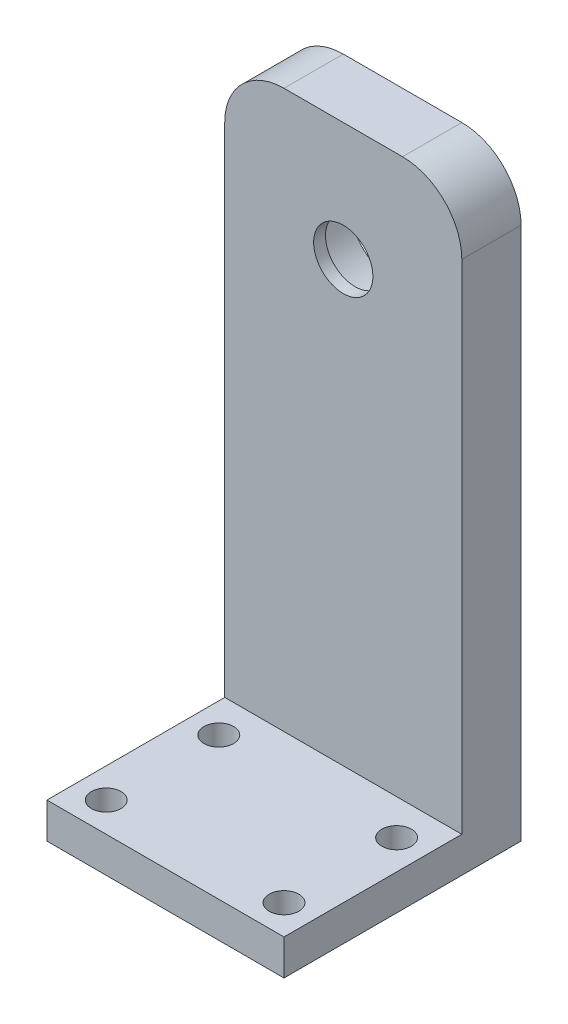
SolidWorks part; units mm, degrees
ref_plane "前视基准面" through (0, 0, 0) normal (0, 0, 1) x (1, 0, 0)
ref_plane "上视基准面" through (0, 0, 0) normal (0, 1, 0) x (1, 0, 0)
ref_plane "右视基准面" through (0, 0, 0) normal (1, 0, 0) x (0, 0, -1)
sketch "草图1" plane through (0, 0, 0) normal (0, 0, 1) x (1, 0, 0)
  line L0 (0, 17.9034) -> (0, -4.2573) construction
  line L1 (-13.2445, 0) -> (15.9947, 0) construction
  line L2 (-20, 15) -> (20, 15)
  line L3 (-20, 15) -> (-20, -15)
  line L4 (-20, -15) -> (20, -15)
  line L5 (20, 15) -> (20, -15)
  dimension "D1" = 40
  dimension "D2" = 30
  dimension "D3" = 20
  dimension "D4" = 15
extrude "凸台-拉伸1" add sketch "草图1" along normal blind 10
sketch "草图2" plane through (0, 0, 10) normal (0, 0, 1) x (1, 0, 0)
  line L0 (0, 19.1713) -> (0, -20.8604) construction
  line L1 (20, 15) -> (17.5, 15)
  line L2 (-5, 10) -> (-12.7402, 10)
  line L3 (20, 15) -> (-20, 15) construction
  line L4 (-20, 15) -> (-20, -15) construction
  line L5 (-20, 12.5) -> (-20, 15)
  line L6 (-20, 15) -> (-17.5, 15)
  line L7 (20, 12.5) -> (20, 15)
  line L9 (-20, -10) -> (20, -10)
  line L10 (-20, -10) -> (-20, -15)
  line L11 (-20, -15) -> (20, -15)
  line L12 (20, -10) -> (20, -15)
  circle A0 centre (0, 5) radius 5
  arc A1 (-17.5, 15) -> (-20, 12.5) centre (-17.5, 12.5) ccw
  arc A2 (17.5, 15) -> (20, 12.5) centre (17.5, 12.5) cw
  line M8 (-20, 15) -> (-20, -15)
  line M9 (-20, -15) -> (20, -15)
  line M10 (20, -15) -> (20, 15)
  line M11 (20, 15) -> (-20, 15)
  dimension "D1" = 10
  dimension "D2" = 5
  dimension "D3" = 15
  dimension "D4" = 10
extrude "切除-拉伸1" cut sketch "草图2" against normal blind 50 contours A1 M11 M8 | L0 A0 | A0 L0 | A2 M11 M10 | L9 L0 L11 M10 | L0 L9 M8 M9
sketch "草图3" plane through (0, 0, 10) normal (0, 0, 1) x (1, 0, 0)
  line L0 (20, -10) -> (20, 12.5) construction
  line L1 (-20, -10) -> (20, -10)
  line L2 (-20, -10) -> (-20, -2)
  line L3 (-20, -2) -> (20, -2)
  line L4 (20, -10) -> (20, -2)
  dimension "D1" = 8
extrude "凸台-拉伸2" add sketch "草图3" along normal blind 30
sketch "草图4" plane through (0, 0, 40) normal (0, 0, 1) x (1, 0, 0)
  line L0 (20, -10) -> (20, -2) construction
  line L1 (-20, -10) -> (20, -10)
  line L2 (-20, -10) -> (-20, -8)
  line L3 (-20, -8) -> (20, -8)
  line L4 (20, -10) -> (20, -8)
  dimension "D1" = 2
extrude "切除-拉伸2" cut sketch "草图4" against normal through all
sketch "草图5" plane through (0, -2, 0) normal (0, 1, 0) x (1, 0, 0)
  line L0 (-15, 1.0779) -> (-15, -18.9875) construction
  line L1 (15, 1.6229) -> (15, -19.1362) construction
  line L2 (20, -40) -> (20, -10) construction
  line L3 (-20, -40) -> (-20, -10) construction
  line L4 (-12.0888, -35) -> (11.8658, -35) construction
  line L5 (20, -40) -> (-20, -40) construction
  circle A0 centre (-15, -35) radius 2.5
  circle A1 centre (15, -35) radius 2.5
  point P12 (-15, -35)
  point P13 (15, -35)
  dimension "D4" = 5
  dimension "D5" = 5
  dimension "D1" = 5
  dimension "D2" = 5
  dimension "D3" = 5
extrude "切除-拉伸3" cut sketch "草图5" against normal blind 15
sketch "草图7" plane through (0, -2, 0) normal (0, 1, 0) x (1, 0, 0)
  line L0 (-15, -36.9484) -> (-15, 4.9474) construction
  line L1 (20, -10) -> (-20, -10) construction
  line L2 (15, -35.0847) -> (15, 6.6835) construction
  line L3 (17.5, -10) -> (-17.5, -10) construction
  circle A0 centre (-15, -16) radius 2.5
  circle A1 centre (15, -16) radius 2.5
  dimension "D1" = 5
  dimension "D3" = 5
  dimension "D2" = 6
  dimension "D4" = 6
extrude "切除-拉伸4" cut sketch "草图7" against normal blind 15
sketch "草图8" plane through (0, 0, 0) normal (0, 0, -1) x (-1, 0, 0)
  line L1 (-20, -8) -> (20, -8)
  line L2 (-20, -8) -> (-20, 92)
  line L3 (-20, 92) -> (20, 92)
  line L4 (20, -8) -> (20, 92)
  dimension "D1" = 100
extrude "凸台-拉伸3" add sketch "草图8" against normal up to surface (10 mm away) up to face at (0, 8.6726, 10)
sketch "草图9" plane through (0, 0, 0) normal (0, 0, -1) x (-1, 0, 0)
  line L0 (0, 96.0683) -> (0, -23.4772) construction
  line L1 (-20, -8) -> (20, -8) construction
  circle A0 centre (0, 72) radius 5
  dimension "D1" = 10
  dimension "D2" = 80
extrude "切除-拉伸5" cut sketch "草图9" against normal through all
fillet "圆角1" radius 10 2 edges at (-20, 92, 5) (20, 92, 5)
sketch "草图13" plane through (0, 0, 10) normal (0, 0, 1) x (1, 0, 0)
  circle A0 centre (0, 72) radius 9.5
  dimension "D1" = 19
extrude "切除-拉伸8" cut sketch "草图13" against normal through all
sketch "草图14" plane through (0, 0, 10) normal (0, 0, 1) x (1, 0, 0)
  circle A0 centre (0, 72) radius 9.5
  circle A1 centre (0, 72) radius 5
  dimension "D1" = 19
  dimension "D2" = 10
extrude "凸台-拉伸5" add sketch "草图14" against normal blind 2
